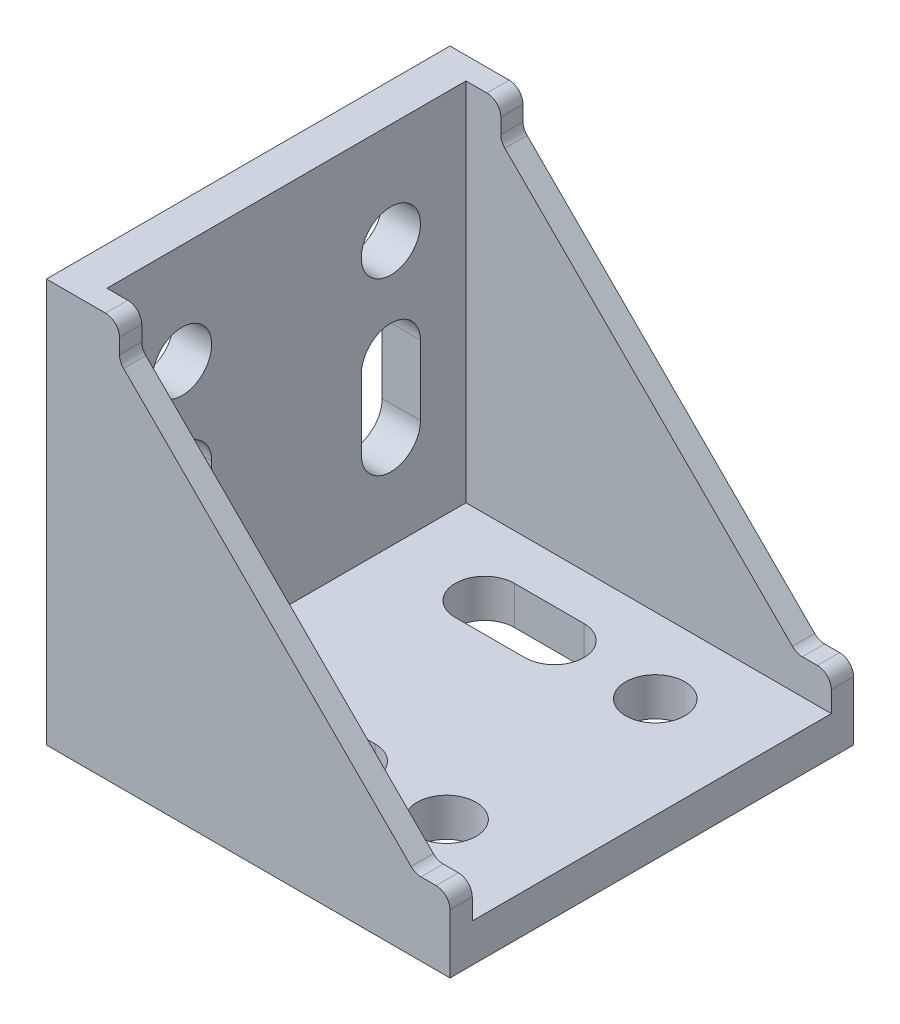
SolidWorks part; units mm, degrees
ref_plane "前视基准面" through (0, 0, 0) normal (0, 0, 1) x (1, 0, 0)
ref_plane "上视基准面" through (0, 0, 0) normal (0, 1, 0) x (1, 0, 0)
ref_plane "右视基准面" through (0, 0, 0) normal (1, 0, 0) x (0, 0, -1)
other "Configuration Table"
sketch "草图1" plane through (0, 0, 0) normal (0, 0, 1) x (1, 0, 0)
  line L0 (0, 58) -> (0, 0)
  line L1 (0, 0) -> (58, 0)
  line L2 (58, 0) -> (58, 5.5)
  line L3 (58, 5.5) -> (5.5, 5.5)
  line L4 (5.5, 5.5) -> (5.5, 58)
  line L5 (5.5, 58) -> (0, 58)
  dimension "D1" = 58
  dimension "D2" = 58
  dimension "D3" = 5.5
  dimension "D4" = 5.5
extrude "凸台-拉伸1" add sketch "草图1" along normal blind 58
sketch "草图2" plane through (0, 0, 0) normal (0, -1, 0) x (1, 0, 0)
  line L0 (-9.19, 29) -> (73.7136, 29) construction
  line L1 (0, 58) -> (58, 58) construction
  line L2 (0, 0) -> (58, 0) construction
  line L3 (19, 48.25) -> (29, 48.25)
  line L4 (19, 39.75) -> (29, 39.75)
  line L6 (19, 9.75) -> (29, 9.75)
  line L7 (19, 18.25) -> (29, 18.25)
  line L9 (58, 58) -> (58, 0) construction
  circle A0 centre (43.5, 44) radius 4.25
  arc A1 (29, 39.75) -> (29, 48.25) centre (29, 44) ccw
  arc A2 (19, 48.25) -> (19, 39.75) centre (19, 44) ccw
  arc A3 (19, 9.75) -> (19, 18.25) centre (19, 14) cw
  arc A4 (29, 18.25) -> (29, 9.75) centre (29, 14) cw
  circle A5 centre (43.5, 14) radius 4.25
  point P16 (0, 0)
  point P17 (0, 0)
  dimension "D1" = 8.5
  dimension "D2" = 8.5
  dimension "D3" = 8.5
  dimension "D4" = 14.5
  dimension "D5" = 15
  dimension "D6" = 10
  dimension "D7" = 14.5
extrude "切除-拉伸1" cut sketch "草图2" against normal blind 58.5
sketch "草图3" plane through (0, 0, 0) normal (-1, 0, 0) x (0, 0, 1)
  line L0 (29, 59.3136) -> (29, -3.259) construction
  line L1 (58, 58) -> (58, 0) construction
  line L2 (0, 58) -> (0, 0) construction
  line L3 (39.75, 29) -> (39.75, 19)
  line L4 (48.25, 29) -> (48.25, 19)
  line L5 (58, 58) -> (0, 58) construction
  line L6 (9.75, 29) -> (9.75, 19)
  line L7 (18.25, 29) -> (18.25, 19)
  circle A0 centre (44, 43.5) radius 4.25
  arc A1 (48.25, 29) -> (39.75, 29) centre (44, 29) ccw
  arc A2 (39.75, 19) -> (48.25, 19) centre (44, 19) ccw
  arc A3 (18.25, 19) -> (9.75, 19) centre (14, 19) cw
  arc A4 (9.75, 29) -> (18.25, 29) centre (14, 29) cw
  circle A5 centre (14, 43.5) radius 4.25
  point P16 (0, 0)
  point P17 (0, 0)
  point P18 (0, 0)
  dimension "D1" = 8.5
  dimension "D2" = 8.5
  dimension "D3" = 8.5
  dimension "D4" = 15
  dimension "D5" = 14.5
  dimension "D6" = 14.5
  dimension "D7" = 10
extrude "切除-拉伸2" cut sketch "草图3" against normal blind 58.5
sketch "草图4" plane through (0, 0, 58) normal (0, 0, 1) x (1, 0, 0)
  line L0 (0, 0) -> (47.8757, 47.8757) construction
  line L1 (0, 0) -> (58, 0) construction
  line L2 (5.5, 58) -> (10.5, 58)
  line L3 (10.5, 58) -> (10.5, 53)
  line L4 (10.5, 53) -> (53, 10.5)
  line L5 (58, 10.5) -> (53, 10.5)
  line L6 (58, 5.5) -> (58, 10.5)
  line L7 (5.5, 58) -> (5.5, 5.5)
  line L10 (5.5, 5.5) -> (58, 5.5)
  point P11 (31.75, 31.75)
  point P13 (6.1, 6.1)
  point P15 (11.8353, 6.1)
  point P16 (0, 0)
  dimension "D1" = 45
  dimension "D2" = 5
  dimension "D3" = 5
extrude "凸台-拉伸2" add sketch "草图4" against normal blind 3.2 contours L4 L5 L6 L10 L7 L2 L3
sketch "草图5" plane through (0, 0, 0) normal (0, 0, -1) x (-1, 0, 0)
  line L0 (0, 0) -> (-44.3039, 44.3039) construction
  line L1 (0, 0) -> (-58, 0) construction
  line L9 (-10.5, 58) -> (-10.5, 53)
  line L10 (-10.5, 53) -> (-53, 10.5)
  line L11 (-53, 10.5) -> (-58, 10.5)
  line L12 (-58, 10.5) -> (-58, 5.5)
  line L13 (-58, 5.5) -> (-5.5, 5.5)
  line L14 (-5.5, 5.5) -> (-5.5, 58)
  line L15 (-5.5, 58) -> (-10.5, 58)
  line L16 (-10.5, 58) -> (-10.5, 53)
  line L17 (-10.5, 53) -> (-53, 10.5)
  line L18 (-53, 10.5) -> (-58, 10.5)
  line L19 (-58, 10.5) -> (-58, 5.5)
  line L20 (-58, 5.5) -> (-5.5, 5.5)
  line L21 (-5.5, 5.5) -> (-5.5, 58)
  line L22 (-5.5, 58) -> (-10.5, 58)
  dimension "D1" = 45
  dimension "D2" = 0
extrude "凸台-拉伸3" add sketch "草图5" against normal blind 3.2 contours L17 L18 L19 L20 L21 L22 L16
fillet "圆角1" radius 2 8 edges at (10.5, 58, 56.4) (10.5, 53, 56.4) (53, 10.5, 56.4) (58, 10.5, 56.4) (58, 10.5, 1.6) (53, 10.5, 1.6) (10.5, 53, 1.6) (10.5, 58, 1.6)
